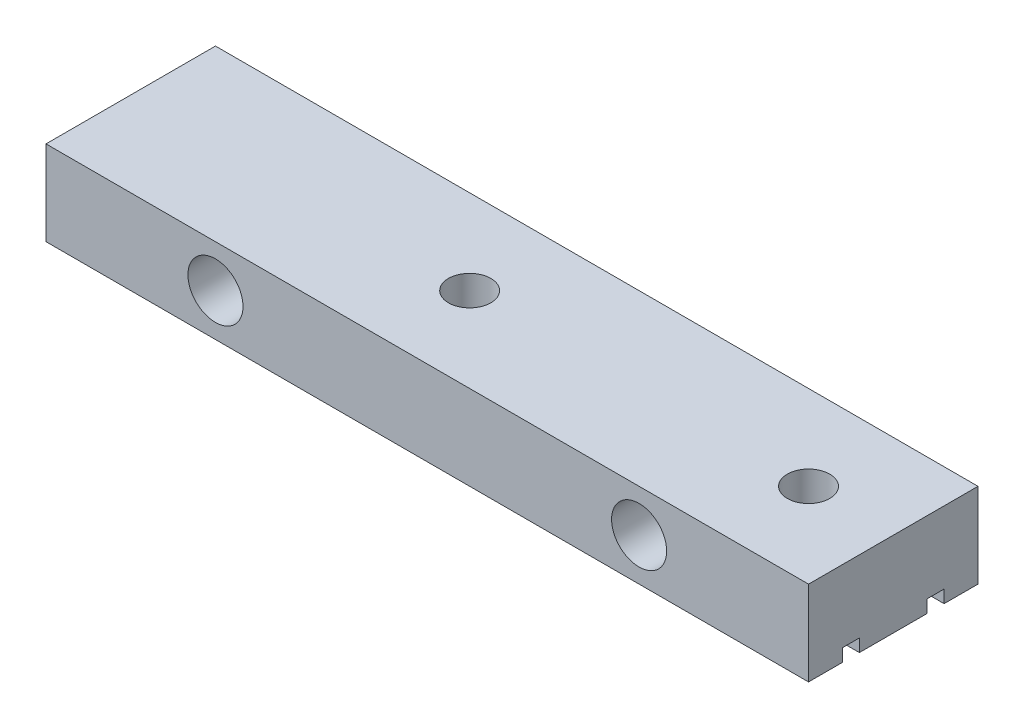
SolidWorks part; units mm, degrees
ref_plane "Ön Düzlem" through (0, 0, 0) normal (0, 0, 1) x (1, 0, 0)
ref_plane "Üst Düzlem" through (0, 0, 0) normal (0, 1, 0) x (1, 0, 0)
ref_plane "Sağ Düzlem" through (0, 0, 0) normal (1, 0, 0) x (0, 0, -1)
sketch "Çizim1" plane through (0, 0, 0) normal (0, 0, 1) x (1, 0, 0)
  line L1 (0, 0) -> (90, 0)
  line L2 (0, 0) -> (0, 10)
  line L3 (0, 10) -> (90, 10)
  line L4 (90, 0) -> (90, 10)
  dimension "D4" = 10
extrude "Yükseklik-Ekstrüzyon1" add sketch "Çizim1" along normal blind 20
sketch "Çizim6" plane through (0, 0, 0) normal (-1, 0, 0) x (0, 0, 1)
  line L0 (20, 0) -> (0, 0) construction
  line L1 (0, 10) -> (0, 0) construction
  line L2 (4, 0) -> (6, 0)
  line L3 (4, 0) -> (4, 1.5)
  line L4 (4, 1.5) -> (6, 1.5)
  line L5 (6, 0) -> (6, 1.5)
  line L6 (14, 0) -> (16, 0)
  line L7 (14, 0) -> (14, 1.5)
  line L8 (14, 1.5) -> (16, 1.5)
  line L9 (16, 0) -> (16, 1.5)
  line L10 (20, 10) -> (20, 0) construction
  dimension "D1" = 4
  dimension "D2" = 4
  dimension "D3" = 2
  dimension "D4" = 2
  dimension "D5" = 1.5
extrude "Kes-Ekstrüzyon1" cut sketch "Çizim6" against normal through all
sketch "Çizim10" plane through (0, 10, 0) normal (0, 1, 0) x (1, 0, 0)
  line L0 (0, -10) -> (90, -10) construction
  line L1 (0, -20) -> (0, 0) construction
  line L2 (90, -20) -> (90, 0) construction
  point P6 (40, -10)
  point P7 (80, -10)
  dimension "D1" = 40
  dimension "D2" = 40
hole_wizard "Ø4.0mm Saplama Delikleri3" positions "3B Çizim4" profile "Çizim11" hole size "Ø4.0" standard "ANSI Metric"
sketch3d "3B Çizim4"
  point P0 (40, 10, 10)
  point P3 (80, 10, 10)
sketch "Çizim11" plane through (40, 10, 10) normal (1, 0, 0) x (0, 0, 1)
  line L0 (0, 0) -> (0, 8)
  line L1 (0, 8) -> (2.5, 8)
  line L2 (2.5, 8) -> (2.5, 0)
  line L5 (2.5, 0) -> (0, 0)
  line L10 (0, 8) -> (-2.5, 8) construction
  line L11 (0, -6.35) -> (0, 107.95) construction
  dimension "Hole Dia." = 5
  dimension "Hole Depth" = 8
  dimension "Drill Angle" = 180
sketch "Çizim13" plane through (0, 0, 20) normal (0, 0, 1) x (1, 0, 0)
  line L0 (0, 5) -> (90, 5) construction
  line L1 (0, 10) -> (0, 0) construction
  line L2 (90, 0) -> (90, 10) construction
  circle A0 centre (20, 5) radius 3.25
  circle A1 centre (70, 5) radius 3.25
  point P6 (20, 5)
  point P7 (70, 5)
  dimension "D1" = 20
  dimension "D2" = 50
sketch "Çizim14" plane through (0, 0, 20) normal (0, 0, 1) x (1, 0, 0)
  circle A0 centre (20, 5) radius 2
  circle A1 centre (70, 5) radius 2
extrude "Kes-Ekstrüzyon2" cut sketch "Çizim14" against normal through all
extrude "Kes-Ekstrüzyon4" cut sketch "Çizim13" against normal blind 6 contours A1 | A0
sketch "Çizim15" plane through (0, 0, 0) normal (0, 0, -1) x (-1, 0, 0)
  circle A0 centre (-70, 5) radius 3.25
  circle A1 centre (-20, 5) radius 3.25
extrude "Kes-Ekstrüzyon5" cut sketch "Çizim15" against normal blind 6
